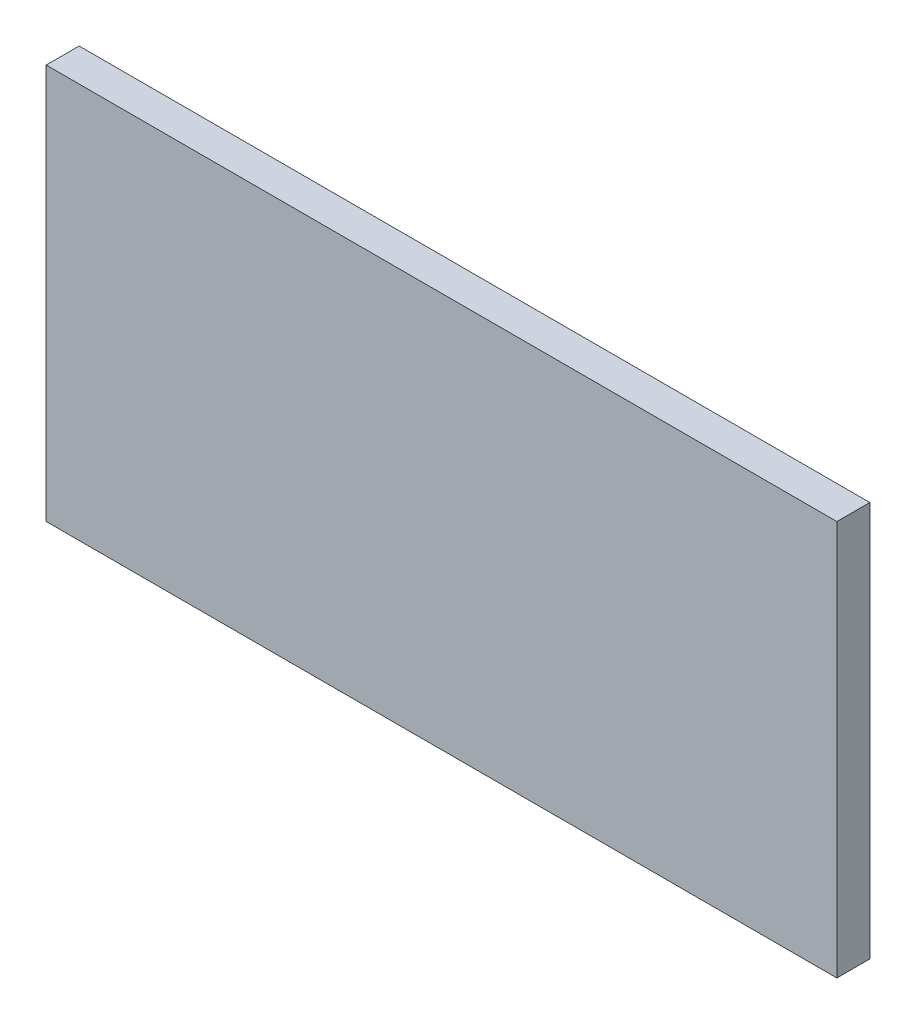
SolidWorks part; units mm, degrees
ref_plane "Front Plane" through (0, 0, 0) normal (0, 0, 1) x (1, 0, 0)
ref_plane "Top Plane" through (0, 0, 0) normal (0, 1, 0) x (1, 0, 0)
ref_plane "Right Plane" through (0, 0, 0) normal (1, 0, 0) x (0, 0, -1)
sketch "Sketch1" plane through (0, 0, 0) normal (0, 0, 1) x (1, 0, 0)
  line L1 (-6.0795, 5.5033) -> (17.9205, 5.5033)
  line L2 (-6.0795, 5.5033) -> (-6.0795, -6.4967)
  line L3 (-6.0795, -6.4967) -> (17.9205, -6.4967)
  line L4 (17.9205, 5.5033) -> (17.9205, -6.4967)
  dimension "D1" = 12
  dimension "D2" = 24
extrude "Boss-Extrude1" add sketch "Sketch1" along normal blind 1
